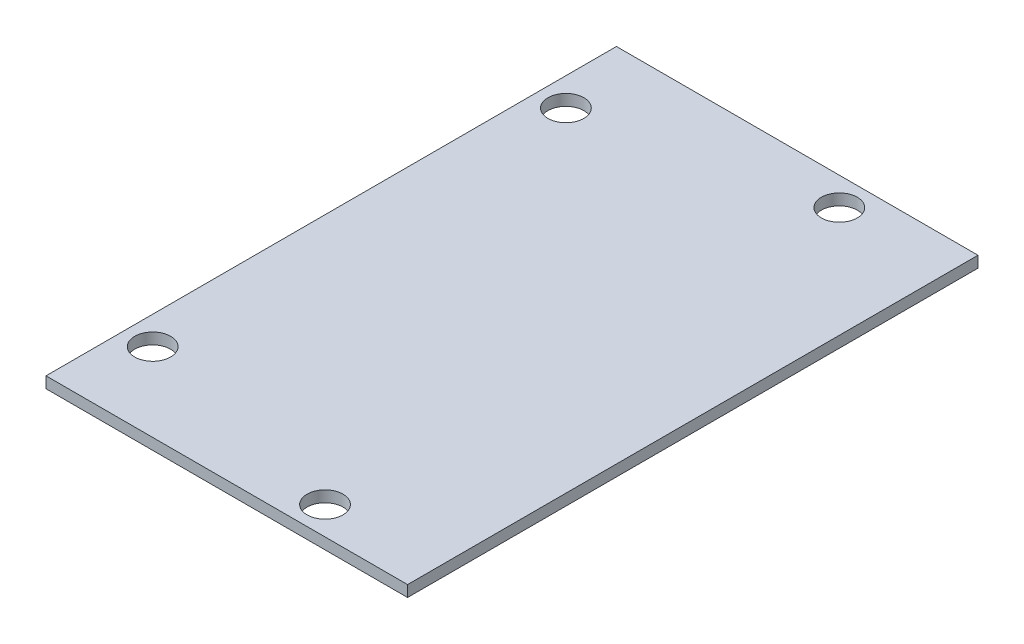
SolidWorks part; units mm, degrees
material "Alliage 1060"
ref_plane "Plan de face" through (0, 0, 0) normal (0, 0, 1) x (1, 0, 0)
ref_plane "Plan de dessus" through (0, 0, 0) normal (0, 1, 0) x (1, 0, 0)
ref_plane "Plan de droite" through (0, 0, 0) normal (1, 0, 0) x (0, 0, -1)
sketch "Esquisse1" plane through (0, 0, 0) normal (0, 1, 0) x (1, 0, 0)
  line L0 (9.85, -35.8) -> (-17.35, -35.8) construction
  line L1 (-22.35, 15) -> (9.85, 15)
  line L2 (-22.35, 15) -> (-22.35, -35.8)
  line L3 (-22.35, -35.8) -> (9.85, -35.8)
  line L4 (9.85, 15) -> (9.85, -35.8)
  line L5 (-22.35, -35.8) -> (-22.35, 15) construction
  line L6 (9.85, 15) -> (-17.35, 15) construction
  line L7 (9.85, -35.8) -> (9.85, -30.8) construction
  circle A0 centre (0, -33.3) radius 1.6
  circle A1 centre (0, 12.5) radius 1.6
  circle A2 centre (-19.85, 8) radius 1.6
  circle A3 centre (-19.85, -28.8) radius 1.6
  dimension "D1" = 3.2
  dimension "D7" = 7
  dimension "D3" = 2.5
  dimension "D4" = 2.5
  dimension "D5" = 2.5
  dimension "D6" = 7
extrude "Extrusion1" add sketch "Esquisse1" along normal blind 1
